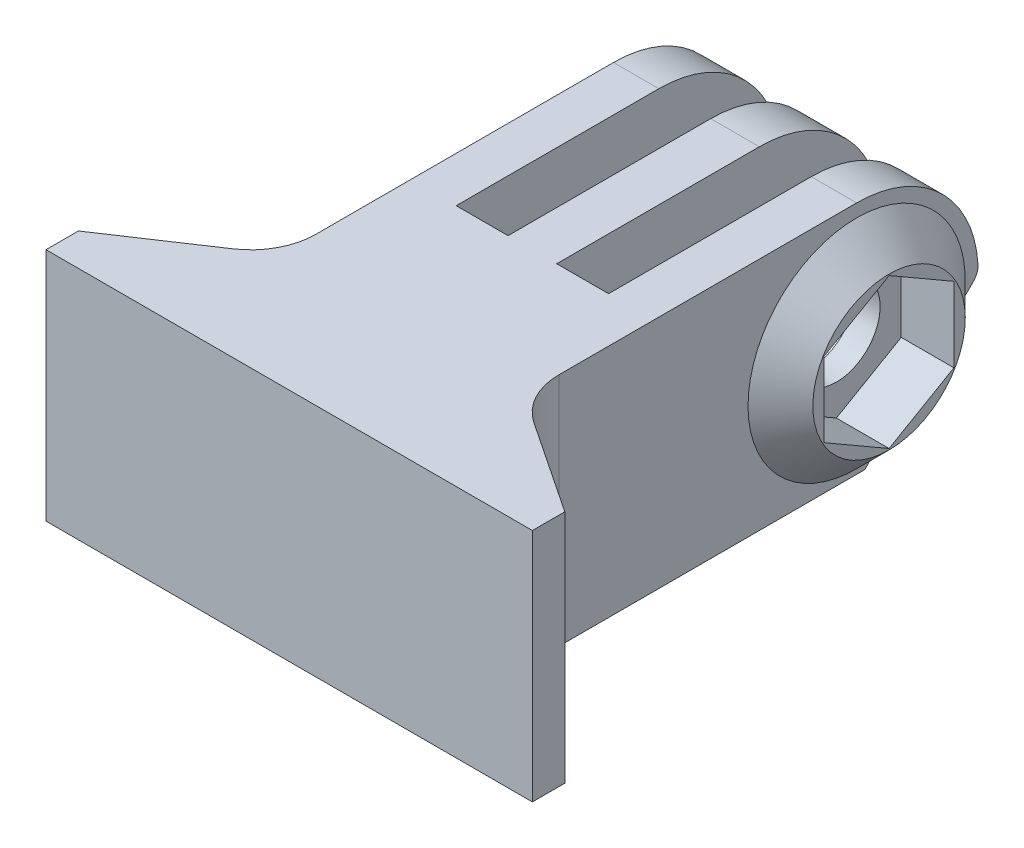
SolidWorks part; units mm, degrees
ref_plane "Front Plane" through (0, 0, 0) normal (0, 0, 1) x (1, 0, 0)
ref_plane "Top Plane" through (0, 0, 0) normal (0, 1, 0) x (1, 0, 0)
ref_plane "Right Plane" through (0, 0, 0) normal (1, 0, 0) x (0, 0, -1)
sketch "Sketch1" plane through (0, 0, 0) normal (1, 0, 0) x (0, 0, -1)
  line L0 (0, 7.5) -> (-20.5, 7.5)
  line L1 (0, -7.5) -> (-20.5, -7.5)
  line L2 (-20.5, -7.5) -> (-20.5, 7.5)
  circle A0 centre (0, 0) radius 2.7
  arc A1 (0, -7.5) -> (0, 7.5) centre (0, 0) ccw
  point P3 (7.5, 0)
  dimension "D1" = 5.4
  dimension "D2" = 15
  dimension "D3" = 28
extrude "main boss" add sketch "Sketch1" along normal blind 15
sketch "Sketch6" plane through (0, 0, 0) normal (0, 1, 0) x (1, 0, 0)
  line L0 (15, 2.7) -> (15, 6.7)
  line L1 (15, 0) -> (15, 7.5) construction
  line L2 (15, 6.7) -> (17, 4.7)
  line L3 (17, 4.7) -> (17, 2.7)
  line L4 (17, 2.7) -> (15, 2.7)
  dimension "D1" = 2
  dimension "D2" = 45
  dimension "D3" = 2
revolve "revolve nut seat" add sketch "Sketch6" angle 360 about axis through (15.75, 0, 0) along (-1, 0, 0)
sketch "Sketch2" plane through (0, 7.5, 0) normal (0, 1, 0) x (1, 0, 0)
  line L0 (15, 7.5) -> (0, 7.5) construction
  line L1 (2.8, 7.5) -> (6, 7.5)
  line L2 (2.8, 7.5) -> (2.8, -10.5)
  line L3 (2.8, -10.5) -> (6, -10.5)
  line L4 (6, 7.5) -> (6, -10.5)
  line L5 (6, -10.5) -> (9, -10.5) construction
  line L6 (9, 7.5) -> (12.2, 7.5)
  line L7 (9, 7.5) -> (9, -10.5)
  line L8 (9, -10.5) -> (12.2, -10.5)
  line L9 (12.2, 7.5) -> (12.2, -10.5)
  line L10 (15, 0) -> (15, 7.5) construction
  line L11 (0, 7.5) -> (0, 0) construction
  line L12 (15, -20.5) -> (0, -20.5) construction
  point P14 (7.5, -10.5)
  point P17 (7.5, -20.5)
  dimension "D1" = 18
  dimension "D2" = 2.8
  dimension "D3" = 2.8
  dimension "D4" = 3
extrude "cut fingers" cut sketch "Sketch2" against normal through all
sketch "Sketch3" plane through (0, 0, 0) normal (1, 0, 0) x (0, 0, -1)
  line L0 (0, -7.5) -> (7.5, 0)
  line L1 (0, -7.5) -> (7.5, -7.5)
  line L2 (7.5, -7.5) -> (7.5, 0)
  arc A0 (0, -7.5) -> (0, 7.5) centre (0, 0) ccw construction
extrude "cut slant" cut sketch "Sketch3" along normal through all
fillet "Fillet1" radius 1 3 edges at (1.4, 0, -7.5) (7.5, 0, -7.5) (13.6, 0, -7.5)
ref_axis "Axis1" through (15.75, 0, 0) along (-1, 0, 0)
sketch "Sketch4" plane through (0, 0, 0) normal (1, 0, 0) x (0, 0, -1)
  line L0 (-1.9092, 1.9092) -> (0, 3.8184)
  line L1 (0, 3.8184) -> (1.9092, 1.9092)
  circle A0 centre (0, 0) radius 2.7 construction
  arc A1 (1.9092, 1.9092) -> (-1.9092, 1.9092) centre (0, 0) cw
extrude "Cut-Extrude3" cut sketch "Sketch4" along normal through all
sketch "Sketch7" plane through (17, 0, 0) normal (1, 0, 0) x (0, 0, -1)
  line L1 (0, 4.6188) -> (-4, 2.3094)
  line L2 (-4, 2.3094) -> (-4, -2.3094)
  line L3 (-4, -2.3094) -> (0, -4.6188)
  line L4 (0, -4.6188) -> (4, -2.3094)
  line L5 (4, -2.3094) -> (4, 2.3094)
  line L6 (4, 2.3094) -> (0, 4.6188)
  circle A0 centre (0, 0) radius 4 construction
  dimension "D1" = 8
extrude "Cut-Extrude4" cut sketch "Sketch7" against normal blind 3.25
sketch "Sketch8" plane through (0, 7.5, 0) normal (0, 1, 0) x (1, 0, 0)
  line L0 (0, -20.5) -> (-7.5, -25.5)
  line L1 (-7.5, -25.5) -> (-7.5, -27.5)
  line L2 (-7.5, -27.5) -> (22.5, -27.5)
  line L3 (22.5, -27.5) -> (22.5, -25.5)
  line L4 (22.5, -25.5) -> (15, -20.5)
  line L5 (15, -20.5) -> (0, -20.5)
  point P3 (7.5, -27.5)
  point P9 (7.5, -20.5)
  dimension "D1" = 30
  dimension "D2" = 2
  dimension "D3" = 7
extrude "Boss-Extrude2" add sketch "Sketch8" against normal up to surface (15 mm away) up to face at (7.5, -7.5, 6.9167)
fillet "Fillet2" radius 4 2 edges at (15, 0, 20.5) (0, 0, 20.5)
chamfer "Chamfer1" distance 0.5 angle 45 9 edges at (0, -7.5, 9.1796) (15, -7.5, 9.1796) (-0.4733, -7.5, 20.2467) (15.4733, -7.5, 20.2467) (-4.6406, -7.5, 23.5937) (-7.5, -7.5, 26.5) (19.6406, -7.5, 23.5937) (22.5, -7.5, 26.5) (7.5, -7.5, 27.5)
sketch "Sketch9" plane through (0, 0, 0) normal (-1, 0, 0) x (0, 0, 1)
  text T0 "v1.1" font "DS ISO 1" height 6
extrude "Cut-Extrude5" cut sketch "Sketch9" against normal blind 0.3
chamfer "Chamfer2" distance 2 angle 45 4 edges at (4.4, -7.5, 10.5) (10.6, -7.5, 10.5) (10.6, 7.5, 10.5) (4.4, 7.5, 10.5)
ref_plane "Plane1" through (7.5, 0, 0) normal (-1, 0, 0) x (0, 0, 1)
